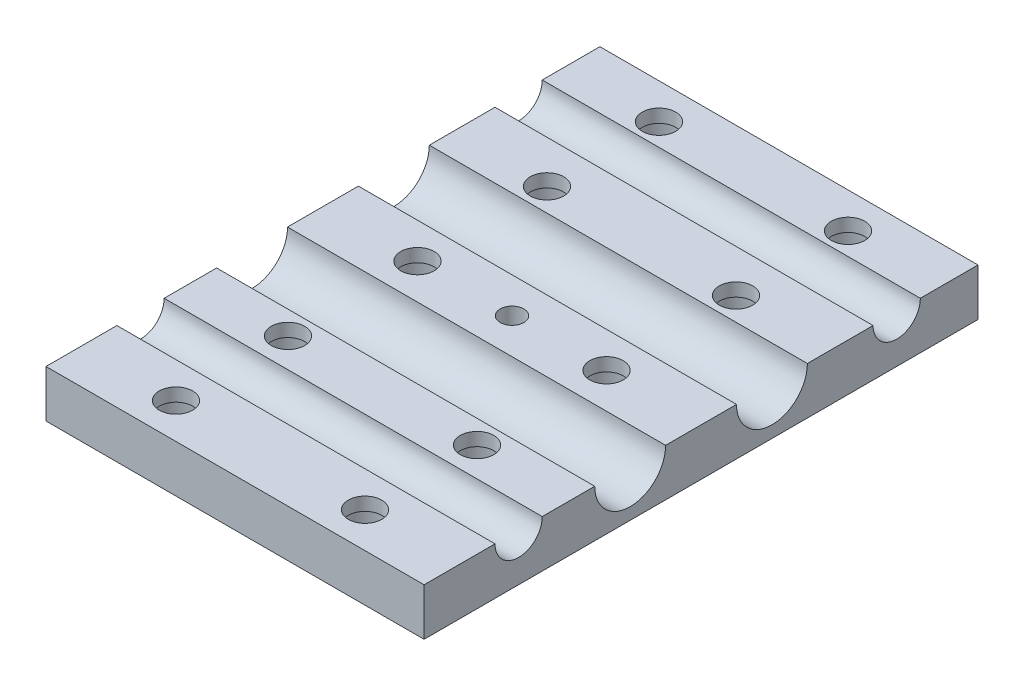
SolidWorks part; units mm, degrees
material "Copper"
ref_plane "Front Plane" through (0, 0, 0) normal (0, 0, 1) x (1, 0, 0)
ref_plane "Top Plane" through (0, 0, 0) normal (0, 1, 0) x (1, 0, 0)
ref_plane "Right Plane" through (0, 0, 0) normal (1, 0, 0) x (0, 0, -1)
sketch "Sketch1" plane through (0, 0, 0) normal (0, 1, 0) x (1, 0, 0)
  line L1 (-37.211, 25.4) -> (37.211, 25.4)
  line L2 (-37.211, 25.4) -> (-37.211, -25.4)
  line L3 (-37.211, -25.4) -> (37.211, -25.4)
  line L4 (37.211, 25.4) -> (37.211, -25.4)
  dimension "D1" = 50.8
  dimension "D2" = 74.422
  dimension "D3" = 37.211
  dimension "D4" = 25.4
extrude "Boss-Extrude1" add sketch "Sketch1" along normal blind 6.35
sketch "Sketch2" plane through (0, 0, 25.4) normal (0, 0, 1) x (1, 0, 0)
  line L0 (-37.211, 0) -> (37.211, 0) construction
  line L1 (-37.211, 6.35) -> (-37.211, 0) construction
  circle A0 centre (-24.511, 0) radius 3.175
  circle A1 centre (26.289, 0) radius 3.175
  dimension "D3" = 6.35
  dimension "D1" = 50.8
  dimension "D2" = 12.7
extrude "Cut-Extrude1" cut sketch "Sketch2" against normal through all
sketch "Sketch3" plane through (0, 0, 25.4) normal (0, 0, 1) x (1, 0, 0)
  line L0 (-21.336, 0) -> (23.114, 0) construction
  circle A0 centre (-9.525, 0) radius 4.7625
  circle A1 centre (9.525, 0) radius 4.7625
  dimension "D1" = 9.525
  dimension "D2" = 19.05
  dimension "D3" = 9.525
extrude "Cut-Extrude2" cut sketch "Sketch3" against normal through all
hole_wizard "#8 Clearance Hole1" positions "Sketch5" profile "Sketch4" hole size "#8" standard "ANSI Inch" end condition through all
sketch "Sketch5" plane through (0, 6.35, 0) normal (0, 1, 0) x (1, 0, 0)
  line L2 (37.211, 25.4) -> (-37.211, 25.4) construction
  line L3 (-37.211, -25.4) -> (37.211, -25.4) construction
  line L4 (-37.211, 25.4) -> (-37.211, -25.4) construction
  line L5 (37.211, -25.4) -> (37.211, 25.4) construction
  point P0 (-32.4485, 12.7)
  point P2 (-32.4485, -12.7)
  point P4 (-17.399, -12.7)
  point P6 (0, -12.7)
  point P8 (17.399, -12.7)
  point P10 (32.4485, -12.7)
  point P12 (32.4485, 12.7)
  point P14 (17.399, 12.7)
  point P16 (0, 12.7)
  point P18 (-17.399, 12.7)
  dimension "D1" = 12.7
  dimension "D2" = 12.7
  dimension "D3" = 4.7625
  dimension "D4" = 4.7625
  dimension "D5" = 19.812
  dimension "D6" = 19.812
sketch "Sketch4" plane through (-32.4485, 6.35, -12.7) normal (1, 0, 0) x (0, 0, 1)
  line L0 (0, 0) -> (0, 6.35)
  line L1 (0, 6.35) -> (2.2479, 6.35)
  line L2 (2.2479, 6.35) -> (2.2479, 0)
  line L5 (2.2479, 0) -> (0, 0)
  line L11 (0, -6.35) -> (0, 107.95) construction
  dimension "Thru Hole Dia." = 4.4958
  dimension "Thru Hole Depth" = 6.35
sketch "Sketch6" plane through (0, 6.35, 0) normal (0, 1, 0) x (1, 0, 0)
  circle A0 centre (-32.4485, 12.7) radius 3.429
  circle A1 centre (-17.399, 12.7) radius 3.429
  circle A2 centre (0, 12.7) radius 3.429
  circle A3 centre (17.399, 12.7) radius 3.429
  circle A4 centre (32.4485, 12.7) radius 3.429
  circle A5 centre (32.4485, -12.7) radius 3.429
  circle A6 centre (17.399, -12.7) radius 3.429
  circle A7 centre (0, -12.7) radius 3.429
  circle A8 centre (-17.399, -12.7) radius 3.429
  circle A9 centre (-32.4485, -12.7) radius 3.429
  dimension "D1" = 6.858
extrude "Cut-Extrude3" cut sketch "Sketch6" against normal blind 4.572
sketch "Sketch7" plane through (0, 6.35, 0) normal (0, 1, 0) x (1, 0, 0)
  circle A0 centre (0, 0) radius 1.5875
  dimension "D1" = 3.175
extrude "Cut-Extrude4" cut sketch "Sketch7" against normal through all
move or copy body "Body-Move/Copy3" bodies to move or copy 110 copy no rotation origin (0, 3.175, 0) rotation axis (0.7071, 0, -0.7071) rotation angle 180
sketch "Sketch8" plane through (0, 6.35, 0) normal (0, 1, 0) x (1, 0, 0)
  line L0 (-25.4, 26.289) -> (25.4, 26.289) construction
  line L1 (-25.4, 29.464) -> (-25.4, 23.114) construction
  line L2 (25.4, 23.114) -> (25.4, 29.464) construction
  line L3 (-25.4, 9.525) -> (25.4, 9.525) construction
  line L4 (-25.4, 14.2875) -> (-25.4, 4.7625) construction
  line L5 (25.4, 4.7625) -> (25.4, 14.2875) construction
  line L6 (-25.4, -9.525) -> (25.4, -9.525) construction
  line L7 (-25.4, -4.7625) -> (-25.4, -14.2875) construction
  line L8 (25.4, -14.2875) -> (25.4, -4.7625) construction
  line L9 (-25.4, -24.511) -> (25.4, -24.511) construction
  line L10 (-25.4, -21.336) -> (-25.4, -27.686) construction
  line L11 (25.4, -27.686) -> (25.4, -21.336) construction
